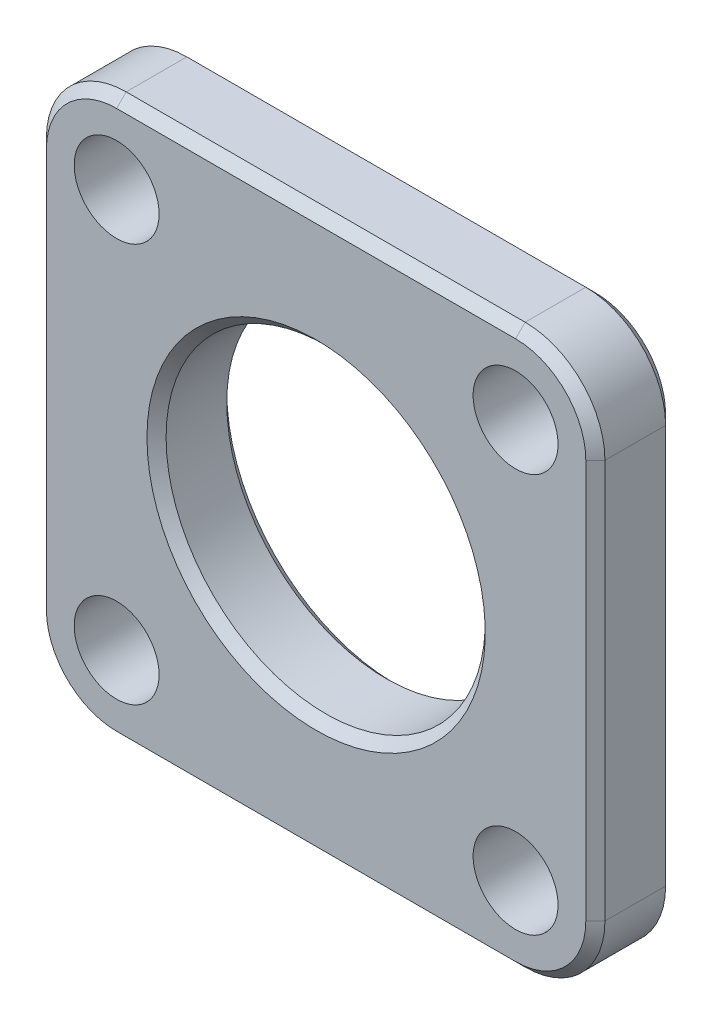
SolidWorks part; units mm, degrees
material "AISI 1020"
ref_plane "Front Plane" through (0, 0, 0) normal (0, 0, 1) x (1, 0, 0)
ref_plane "Top Plane" through (0, 0, 0) normal (0, 1, 0) x (1, 0, 0)
ref_plane "Right Plane" through (0, 0, 0) normal (1, 0, 0) x (0, 0, -1)
sketch "Sketch1" plane through (0, 0, 0) normal (0, 0, 1) x (1, 0, 0)
  line L1 (-15.875, -22.225) -> (15.875, -22.225)
  line L2 (-22.225, -15.875) -> (-22.225, 15.875)
  line L3 (-15.875, 22.225) -> (15.875, 22.225)
  line L4 (22.225, -15.875) -> (22.225, 15.875)
  line L5 (-22.225, -22.225) -> (22.225, 22.225) construction
  line L6 (-22.225, 22.225) -> (22.225, -22.225) construction
  arc A0 (-15.875, -22.225) -> (-22.225, -15.875) centre (-15.875, -15.875) cw
  arc A1 (15.875, -22.225) -> (22.225, -15.875) centre (15.875, -15.875) ccw
  arc A2 (15.875, 22.225) -> (22.225, 15.875) centre (15.875, 15.875) cw
  arc A3 (-22.225, 15.875) -> (-15.875, 22.225) centre (-15.875, 15.875) cw
  circle A4 centre (0, 0) radius 12.7
  point P0 (0, 0)
  dimension "D3" = 6.35
  dimension "D4" = 25.4
  dimension "D1" = 44.45
  dimension "D2" = 44.45
extrude "Boss-Extrude1" add sketch "Sketch1" along normal blind 6.35 contours A3 L3 A2 L4 A1 L1 A0 L2
hole_wizard "1/4 Clearance Hole1" positions "Sketch6" profile "Sketch5" hole size "1/4" standard "ANSI Inch" end condition through all
sketch "Sketch6" plane through (0, 0, 6.35) normal (0, 0, 1) x (1, 0, 0)
  point P0 (-15.875, 15.875)
  point P3 (15.875, -15.875)
  point P5 (15.875, 15.875)
  point P7 (-15.875, -15.875)
sketch "Sketch5" plane through (-15.875, 15.875, 6.35) normal (1, 0, 0) x (0, -1, 0)
  line L0 (0, 0) -> (0, 6.35)
  line L1 (0, 6.35) -> (3.3782, 6.35)
  line L2 (3.3782, 6.35) -> (3.3782, 0)
  line L5 (3.3782, 0) -> (0, 0)
  line L11 (0, -6.35) -> (0, 107.95) construction
  dimension "Thru Hole Dia." = 6.7564
  dimension "Thru Hole Depth" = 6.35
chamfer "Chamfer1" distance 0.762 angle 45 18 edges at (12.7, 0, 0) (12.7, 0, 6.35) (0, -22.225, 0) (20.3651, -20.3651, 0) (-20.3651, -20.3651, 0) (22.225, 0, 0) (-22.225, 0, 0) (20.3651, 20.3651, 0) (-20.3651, 20.3651, 0) (0, 22.225, 0) (0, -22.225, 6.35) (20.3651, -20.3651, 6.35) (-20.3651, -20.3651, 6.35) (22.225, 0, 6.35) (-22.225, 0, 6.35) (20.3651, 20.3651, 6.35) (-20.3651, 20.3651, 6.35) (0, 22.225, 6.35)
